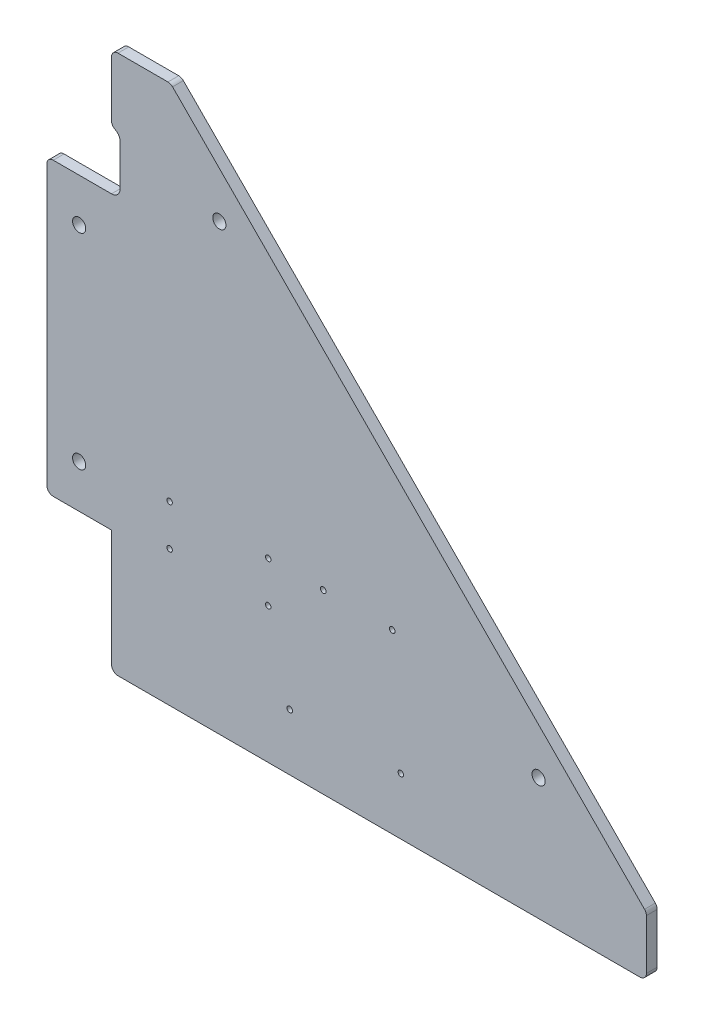
SolidWorks part; units mm, degrees
ref_plane "Front Plane" through (0, 0, 0) normal (0, 0, 1) x (1, 0, 0)
ref_plane "Top Plane" through (0, 0, 0) normal (0, 1, 0) x (1, 0, 0)
ref_plane "Right Plane" through (0, 0, 0) normal (1, 0, 0) x (0, 0, -1)
sketch "Sketch1" plane through (0, 0, 0) normal (0, 0, 1) x (1, 0, 0)
  line L0 (0, 0) -> (0, 135)
  line L1 (0, 135) -> (30, 135)
  line L4 (278, -57) -> (30, -57)
  line L5 (30, -57) -> (30, 0)
  line L6 (30, 0) -> (0, 0)
  line L7 (278, -57) -> (278, -29.57)
  line L8 (278, -29.57) -> (57.43, 193)
  line L9 (57.43, 193) -> (30, 193)
  line L10 (34, 158) -> (34, 139)
  line L11 (30, 193) -> (30, 162)
  line L13 (30, 135) -> (30, 139) construction
  line L14 (30, 139) -> (30, 158) construction
  line L15 (30, 158) -> (30, 162) construction
  line L16 (15, 135) -> (15, 0) construction
  line L17 (58.4642, 170.6468) -> (278, -50.8796) construction
  arc A0 (30, 162) -> (34, 158) centre (30, 158) cw
  arc A1 (30, 135) -> (34, 139) centre (30, 139) ccw
  circle A2 centre (15, 115) radius 3.05
  circle A3 centre (15, 20) radius 3.05
  circle A4 centre (80, 148.9158) radius 3.05
  circle A5 centre (228, -0.4262) radius 3.05
  circle A6 centre (56.9355, 25) radius 1.27
  circle A7 centre (102.6555, 25) radius 1.27
  circle A8 centre (102.6555, 5.95) radius 1.27
  circle A9 centre (56.9355, 5.95) radius 1.27
  dimension "D7" = 4
  dimension "D8" = 27
  dimension "D10" = 6.1
  dimension "D12" = 20
  dimension "D14" = 6.1
  dimension "D15" = 6.1
  dimension "D17" = 50
  dimension "D18" = 2.54
  dimension "D21" = 90
  dimension "D1" = 135
  dimension "D2" = 30
  dimension "D3" = 58
  dimension "D4" = 248
  dimension "D5" = 27.43
  dimension "D6" = 27.43
  dimension "D9" = 31
  dimension "D11" = 20
  dimension "D13" = 15
  dimension "D16" = 50
  dimension "D22" = 57
  dimension "D19" = 2
  dimension "D20" = 2
extrude "Boss-Extrude1" add sketch "Sketch1" along normal blind 5 contours A1 L1 L0 L6 L5 L4 L7 L8 L9 L11 A0 L10 A5 A4 A3 A2
fillet "Fillet1" radius 3 8 edges at (30, 162, 2.5) (30, 193, 2.5) (57.43, 193, 2.5) (278, -29.57, 2.5) (278, -57, 2.5) (30, -57, 2.5) (0, 0, 2.5) (0, 135, 2.5)
sketch "Sketch2" plane through (0, 0, 5) normal (0, 0, 1) x (1, 0, 0)
  line L0 (102.6555, 25) -> (142.1762, 25) construction
  circle A0 centre (112.6555, -30.7) radius 1.3
  circle A1 centre (164.1555, -30.7) radius 1.3
  circle A2 centre (128.1555, 25) radius 1.3
  circle A3 centre (160.1555, 25) radius 1.3
  circle A5 centre (102.6555, 5.95) radius 1.27 construction
  point P8 (0, 0)
  dimension "D1" = 2.6
  dimension "D2" = 2.6
  dimension "D3" = 2.6
  dimension "D4" = 2.6
  dimension "D5" = 51.5
  dimension "D8" = 55.7
  dimension "D7" = 10
  dimension "D9" = 4
  dimension "D6" = 32
extrude "Cut-Extrude1" cut sketch "Sketch2" against normal through all
